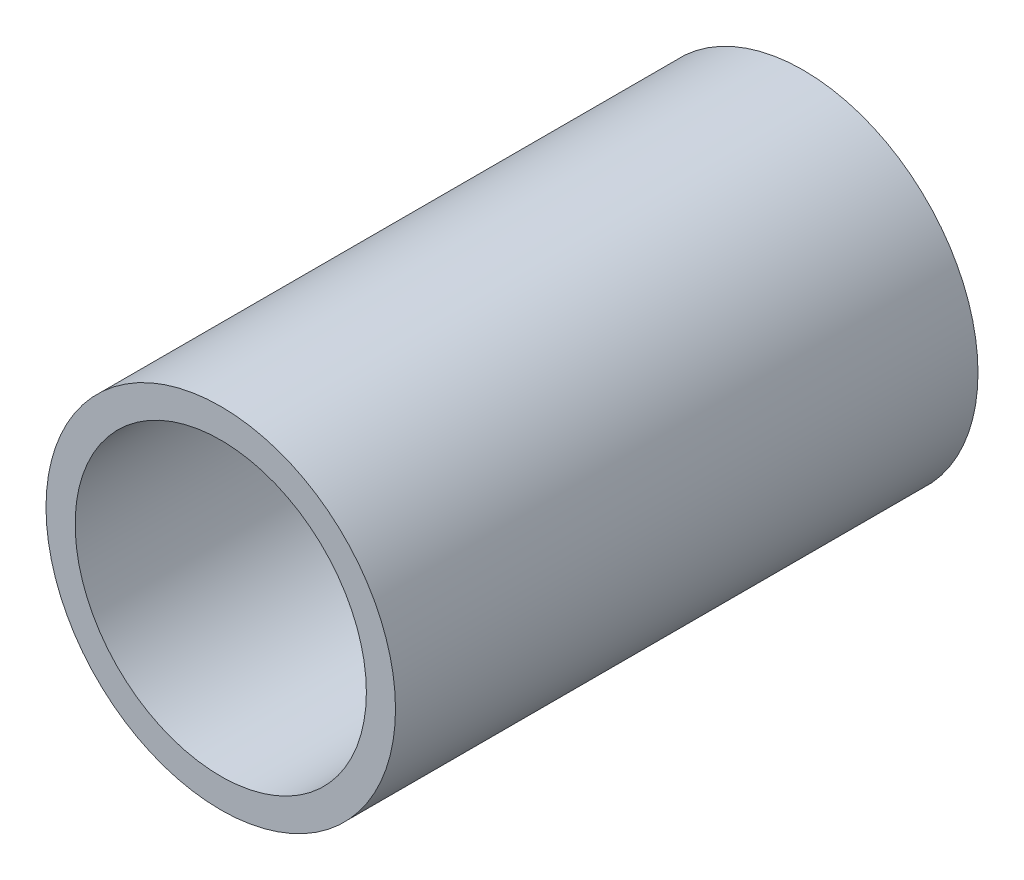
SolidWorks part; units mm, degrees
ref_plane "Front Plane" through (0, 0, 0) normal (0, 0, 1) x (1, 0, 0)
ref_plane "Top Plane" through (0, 0, 0) normal (0, 1, 0) x (1, 0, 0)
ref_plane "Right Plane" through (0, 0, 0) normal (1, 0, 0) x (0, 0, -1)
sketch "Sketch1" plane through (0, 0, 0) normal (0, 0, 1) x (1, 0, 0)
  circle A0 centre (0, 0) radius 6.25
  circle A1 centre (0, 0) radius 7.5
extrude "Boss-Extrude1" add sketch "Sketch1" along normal blind 25
